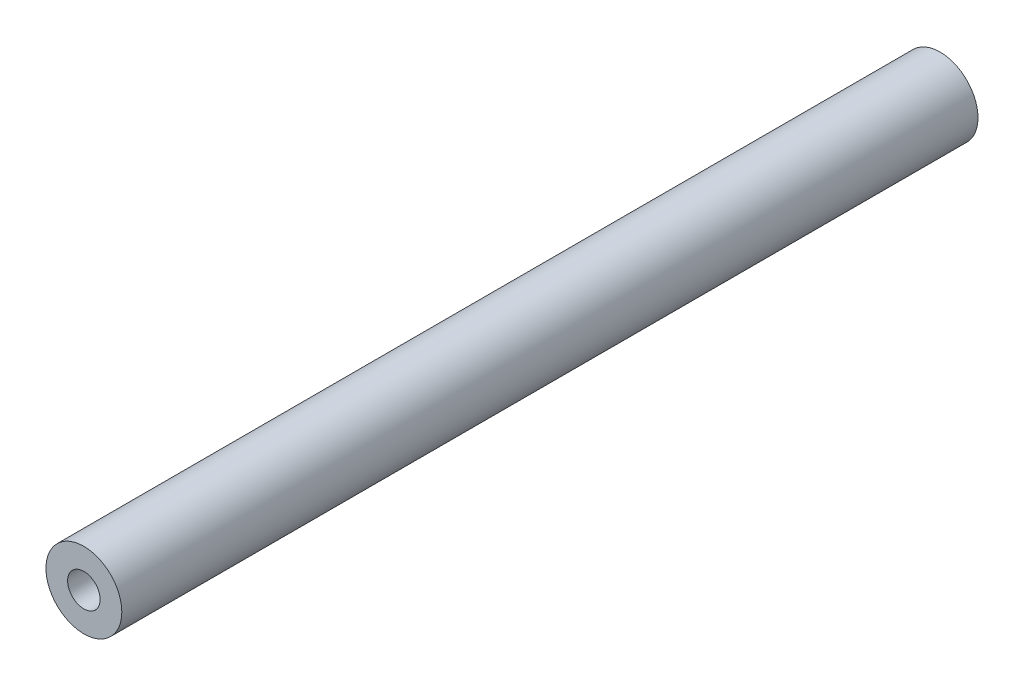
SolidWorks part; units mm, degrees
material "锻制红铜"
ref_plane "前视基准面" through (0, 0, 0) normal (0, 0, 1) x (1, 0, 0)
ref_plane "上视基准面" through (0, 0, 0) normal (0, 1, 0) x (1, 0, 0)
ref_plane "右视基准面" through (0, 0, 0) normal (1, 0, 0) x (0, 0, -1)
sketch "草图1" plane through (0, 0, 0) normal (0, 0, 1) x (1, 0, 0)
  circle A0 centre (0, 0) radius 1.5
  circle A1 centre (0, 0) radius 3.5
  dimension "D1" = 7
  dimension "D2" = 3
extrude "凸台-拉伸1" add sketch "草图1" along normal mid plane 79
